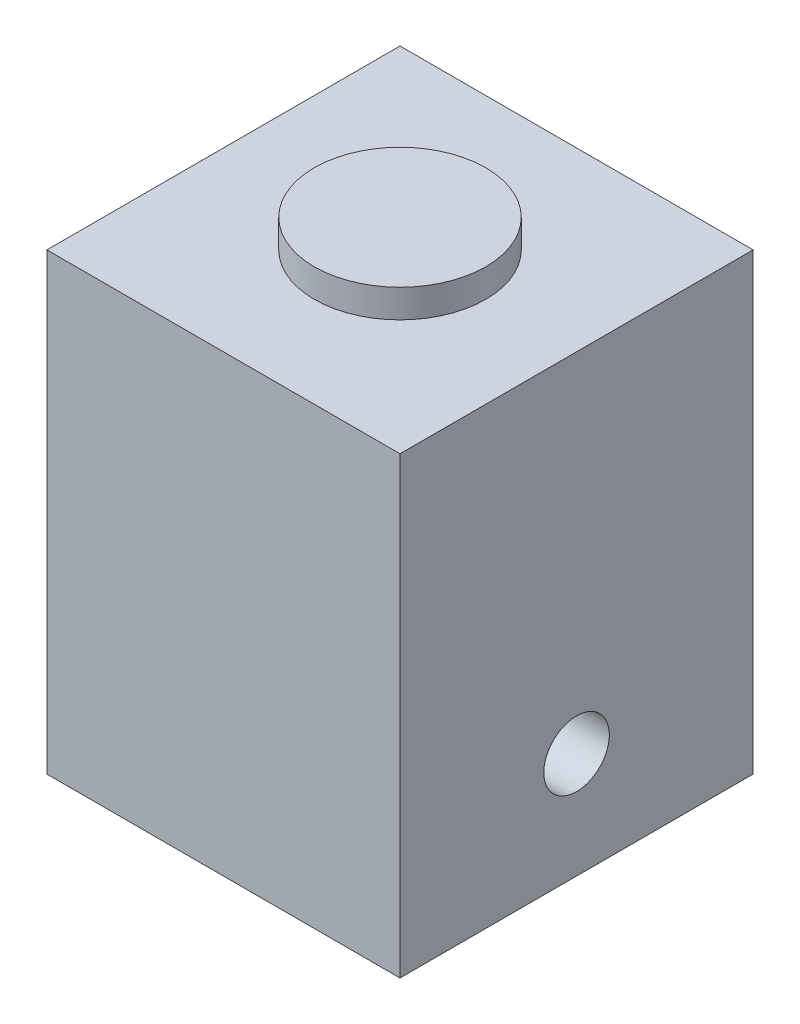
SolidWorks part; units mm, degrees
ref_plane "前视基准面" through (0, 0, 0) normal (0, 0, 1) x (1, 0, 0)
ref_plane "上视基准面" through (0, 0, 0) normal (0, 1, 0) x (1, 0, 0)
ref_plane "右视基准面" through (0, 0, 0) normal (1, 0, 0) x (0, 0, -1)
sketch "草图1" plane through (0, 0, 0) normal (0, 1, 0) x (1, 0, 0)
  line L1 (-17.5, 17.5) -> (17.5, 17.5)
  line L2 (-17.5, 17.5) -> (-17.5, -17.5)
  line L3 (-17.5, -17.5) -> (17.5, -17.5)
  line L4 (17.5, 17.5) -> (17.5, -17.5)
  line L5 (0, -17.5) -> (0, 17.5) construction
  line L6 (-17.5, 0) -> (17.5, 0) construction
  point P0 (0, 0)
  dimension "D1" = 35
  dimension "D2" = 35
extrude "凸台-拉伸1" add sketch "草图1" along normal blind 45
sketch "草图2" plane through (0, 45, 0) normal (0, 1, 0) x (1, 0, 0)
  circle A0 centre (0, 0) radius 8.5
  dimension "D1" = 17
extrude "凸台-拉伸2" add sketch "草图2" along normal blind 2.8
sketch "草图4" plane through (0, 0, 0) normal (0, -1, 0) x (1, 0, 0)
  line L1 (-12, 12) -> (12, 12)
  line L2 (-12, 12) -> (-12, -12)
  line L3 (-12, -12) -> (12, -12)
  line L4 (12, 12) -> (12, -12)
  line L5 (0, -12) -> (0, 12) construction
  line L6 (-12, 0) -> (12, 0) construction
  point P0 (0, 0)
  dimension "D1" = 24
  dimension "D2" = 24
extrude "切除-拉伸1" cut sketch "草图4" against normal blind 40
sketch "草图5" plane through (17.5, 0, 0) normal (1, 0, 0) x (0, 0, -1)
  line L0 (-17.5, 0) -> (17.5, 0) construction
  circle A0 centre (0, 10.5) radius 3.25
  point P4 (0, 0)
  dimension "D1" = 6.5
  dimension "D2" = 10.5
extrude "切除-拉伸2" cut sketch "草图5" against normal through all
